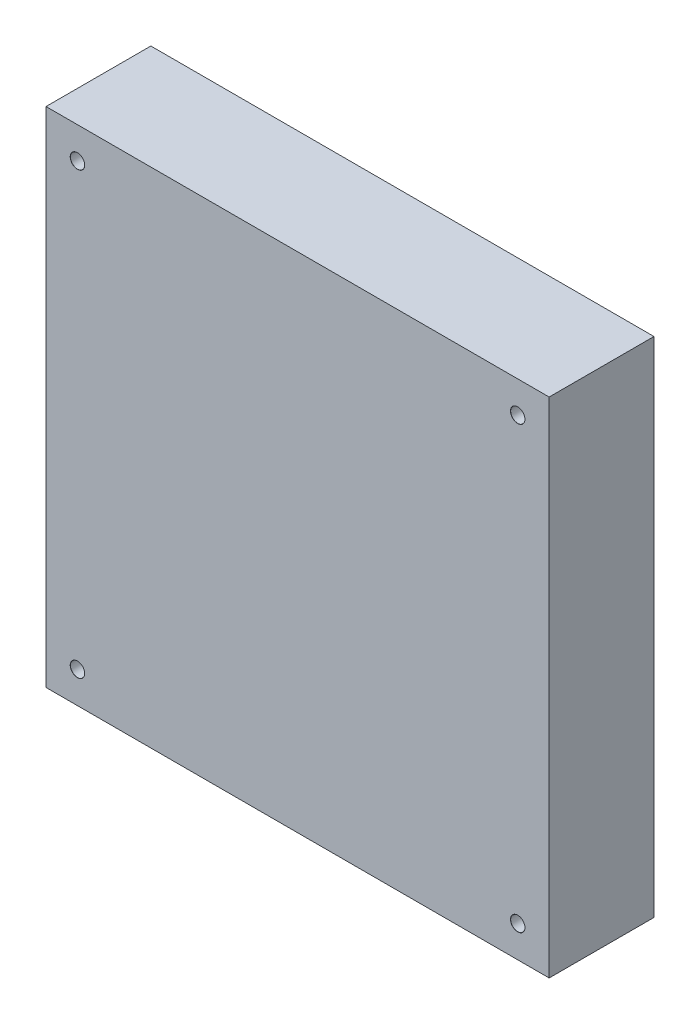
SolidWorks part; units mm, degrees
ref_plane "Front Plane" through (0, 0, 0) normal (0, 0, 1) x (1, 0, 0)
ref_plane "Top Plane" through (0, 0, 0) normal (0, 1, 0) x (1, 0, 0)
ref_plane "Right Plane" through (0, 0, 0) normal (1, 0, 0) x (0, 0, -1)
sketch "Sketch1" plane through (0, 0, 0) normal (0, 0, 1) x (1, 0, 0)
  line L1 (-60, 60) -> (60, 60)
  line L2 (-60, 60) -> (-60, -60)
  line L3 (-60, -60) -> (60, -60)
  line L4 (60, 60) -> (60, -60)
  line L5 (-60, 60) -> (60, -60) construction
  line L6 (-60, -60) -> (60, 60) construction
  point P0 (0, 0)
  dimension "D1" = 120
extrude "Boss-Extrude1" add sketch "Sketch1" along normal blind 25
hole_wizard "M3 Clearance Hole1" positions "Sketch3" profile "Sketch4" hole size "M3" standard "ANSI Metric" end condition up to next
sketch "Sketch3" plane through (0, 0, 25) normal (0, 0, 1) x (1, 0, 0)
  line L0 (-52.5, 52.5) -> (52.5, 52.5) construction
  line L1 (52.5, 52.5) -> (52.5, -52.5) construction
  line L2 (52.5, -52.5) -> (-52.5, -52.5) construction
  line L3 (-52.5, -52.5) -> (-52.5, 52.5) construction
  point P0 (-52.5, 52.5)
  point P2 (52.5, 52.5)
  point P4 (52.5, -52.5)
  point P6 (-52.5, -52.5)
  point P19 (-52.5, 0)
  point P21 (0, 52.5)
  dimension "D1" = 105
  dimension "D2" = 105
sketch "Sketch4" plane through (-52.5, 52.5, 25) normal (1, 0, 0) x (0, -1, 0)
  line L0 (0, 0) -> (0, 25)
  line L1 (0, 25) -> (1.7, 25)
  line L2 (1.7, 25) -> (1.7, 0.021)
  line L3 (1.7, 0.021) -> (1.725, 0)
  line L5 (1.725, 0) -> (0, 0)
  line L6 (-1.7, 0.021) -> (-1.725, 0) construction
  line L11 (0, -6.35) -> (0, 107.95) construction
  dimension "Thru Hole Dia." = 3.4
  dimension "Thru Hole Depth" = 25
  dimension "Near C'Sink Dia." = 3.45
  dimension "Near C'Sink Angle" = 100
